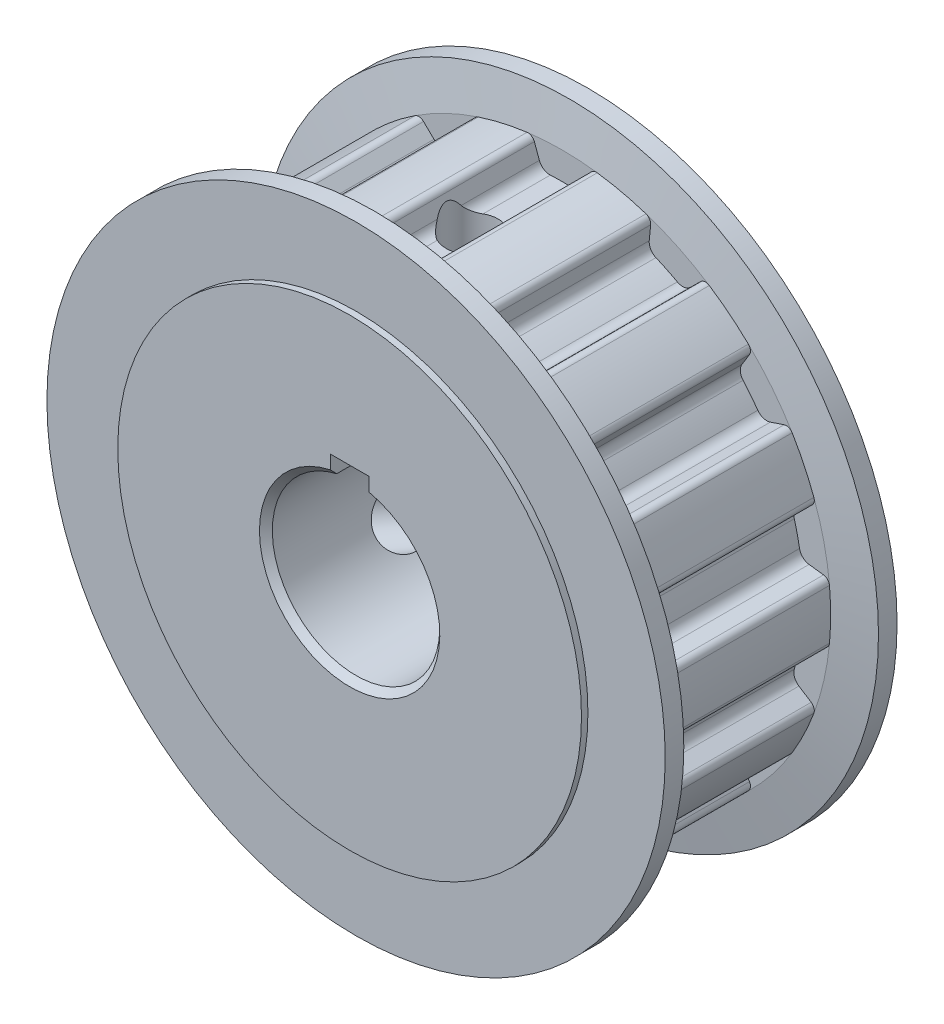
SolidWorks part; units mm, degrees
ref_plane "前视基准面" through (0, 0, 0) normal (0, 0, 1) x (1, 0, 0)
ref_plane "上视基准面" through (0, 0, 0) normal (0, 1, 0) x (1, 0, 0)
ref_plane "右视基准面" through (0, 0, 0) normal (1, 0, 0) x (0, 0, -1)
sketch "草图1" plane through (0, 0, 0) normal (1, 0, 0) x (0, 0, -1)
  line L0 (0, 0) -> (19, 0) construction
  line L1 (18.5, 6.5) -> (0.5, 6.5)
  line L2 (0, 7) -> (0, 18)
  line L5 (19, 18) -> (19, 7)
  line L6 (0.5, 6.5) -> (0, 7)
  line L7 (0, 18) -> (0.5, 18)
  line L8 (0.5, 18) -> (0.5, 24)
  line L9 (0.5, 24) -> (1.9437, 24)
  line L10 (1.9437, 24) -> (2.5, 20.845)
  line L11 (2.5, 20.845) -> (16.5, 20.845)
  line L12 (16.5, 20.845) -> (17.0563, 24)
  line L13 (17.0563, 24) -> (18.5, 24)
  line L14 (18.5, 24) -> (18.5, 18)
  line L15 (18.5, 18) -> (19, 18)
  line L16 (19, 7) -> (18.5, 6.5)
  point P4 (0, 6.5)
  point P9 (19, 6.5)
  dimension "D1" = 0.5
  dimension "d" = 13
  dimension "M" = 36
  dimension "F" = 48
  dimension "D2" = 80
  dimension "K" = 14
  dimension "O.D" = 41.69
  dimension "W" = 19
revolve "旋转1" add sketch "草图1" angle 360 mid plane about L0
sketch "草图2" plane through (0, 0, 0) normal (0, 0, 1) x (1, 0, 0)
  line L0 (0, 0) -> (0, 21.225) construction
  line L1 (-2.1583, 20.3219) -> (-1.7707, 19.2572)
  line L2 (2.1583, 20.3219) -> (1.7707, 19.2572)
  circle A0 centre (0, 0) radius 20.845 construction
  arc A1 (2.7256, 20.666) -> (-2.7256, 20.666) centre (0, 0) ccw
  circle A2 centre (0, 0) radius 21.225 construction
  arc A3 (0.9203, 18.6924) -> (-0.9203, 18.6924) centre (0, 0) ccw
  circle A4 centre (0, 0) radius 18.715 construction
  arc A5 (-2.7256, 20.666) -> (-2.1583, 20.3219) centre (-2.6563, 20.1406) cw
  arc A6 (2.7256, 20.666) -> (2.1583, 20.3219) centre (2.6563, 20.1406) ccw
  circle A7 centre (0, 0) radius 20.845 construction
  arc A8 (1.7707, 19.2572) -> (0.9203, 18.6924) centre (0.9626, 19.5513) cw
  arc A9 (-1.7707, 19.2572) -> (-0.9203, 18.6924) centre (-0.9626, 19.5513) ccw
  point P9 (1.55, 18.6507)
  point P20 (-1.55, 18.6507)
  dimension "D1" = 2.13
  dimension "P.D" = 42.45
  dimension "D4" = 0.53
  dimension "D5" = 0.86
  dimension "D2" = 3.1
  dimension "D3" = 20
extrude "切除-拉伸1" cut sketch "草图2" against normal up to vertex (16.5 mm away) from vertex at -2.5 starting at point (0, 20.845, -2.5)
pattern_circular "阵列(圆周)1" count 14 over 360 about axis through (0, 0, 0) along (0, 0, 1) of "切除-拉伸1"
sketch "草图3" plane through (0, 0, 0) normal (0, 1, 0) x (1, 0, 0)
  circle A0 centre (0, 9.5) radius 2
  dimension "D1" = 9.5
  dimension "M*" = 4
extrude "切除-拉伸2" cut sketch "草图3" along normal through all
cosmetic thread "装饰螺纹线1" parameters "D2"=457
pattern_circular "阵列(圆周)2" count 2 every 120 about axis through (0, 0, 0) along (0, 0, 1) of "切除-拉伸2"
sketch "草图4" plane through (0, 0, 0) normal (0, 0, 1) x (1, 0, 0)
  line L1 (-1.5, 6.3246) -> (1.5, 6.3246)
  line L2 (-1.5, 6.3246) -> (-1.5, 7.9)
  line L3 (-1.5, 7.9) -> (1.5, 7.9)
  line L4 (1.5, 6.3246) -> (1.5, 7.9)
  circle A0 centre (0, 0) radius 6.5 construction
  point P6 (0, 7.9)
  dimension "b" = 3
  dimension "t" = 1.4
extrude "切除-拉伸3" cut sketch "草图4" against normal through all
